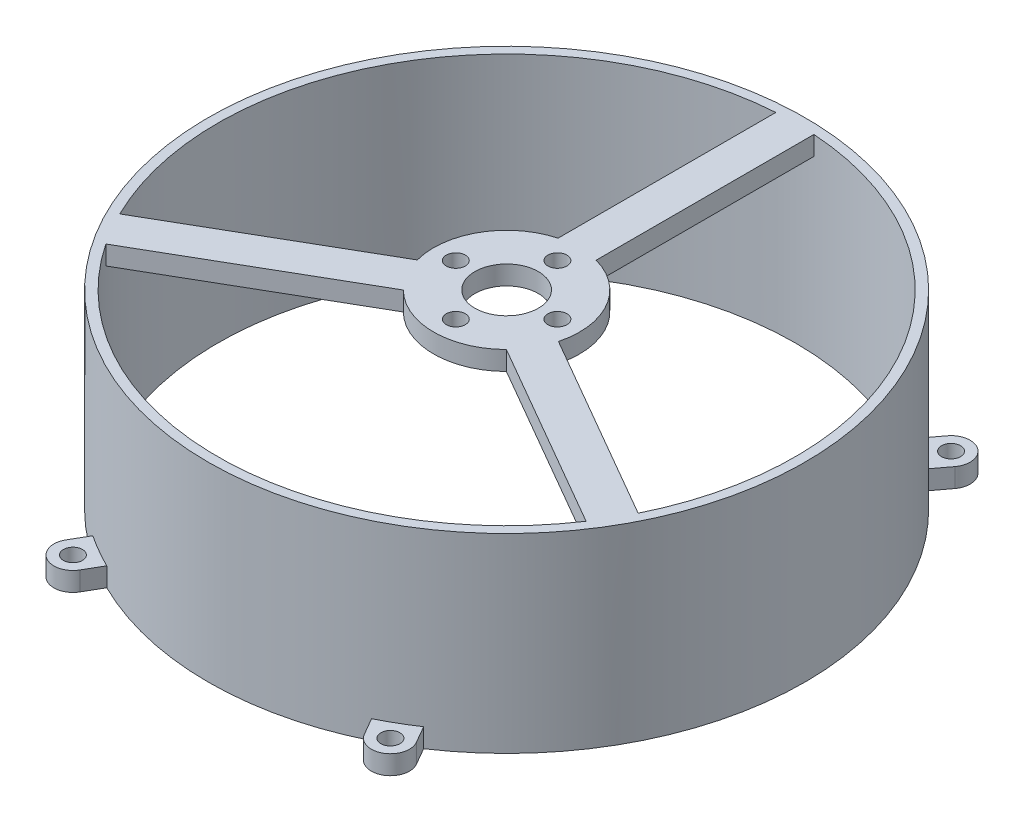
SolidWorks part; units mm, degrees
ref_plane "前视基准面" through (0, 0, 0) normal (0, 0, 1) x (1, 0, 0)
ref_plane "上视基准面" through (0, 0, 0) normal (0, 1, 0) x (1, 0, 0)
ref_plane "右视基准面" through (0, 0, 0) normal (1, 0, 0) x (0, 0, -1)
sketch "草图1" plane through (0, 0, 0) normal (0, 1, 0) x (1, 0, 0)
  circle A21 centre (0, 0) radius 45
  circle A22 centre (0, 0) radius 47
  dimension "D1" = 90
  dimension "D2" = 2
extrude "凸台-拉伸1" add sketch "草图1" along normal blind 30
sketch "草图2" plane through (0, 0, 0) normal (0, -1, 0) x (-1, 0, 0)
  line L0 (25, -43.3013) -> (22.5, -38.9711) construction
  line L1 (22.4019, -44.8013) -> (19.8519, -40.3844)
  line L2 (27.5981, -41.8013) -> (25.048, -37.3844)
  line L3 (0, 0) -> (0, -60.2542) construction
  line L4 (-25, -43.3013) -> (-22.5, -38.9711) construction
  line L5 (-27.5981, -41.8013) -> (-25.048, -37.3844)
  line L6 (-22.4019, -44.8013) -> (-19.8519, -40.3844)
  line L7 (30, 40) -> (27, 36) construction
  line L8 (32.4, 38.2) -> (29.3399, 34.1199)
  line L9 (27.6, 41.8) -> (24.5399, 37.7199)
  line L10 (-30, 40) -> (-27, 36) construction
  line L11 (-27.6, 41.8) -> (-24.5399, 37.7199)
  line L12 (-32.4, 38.2) -> (-29.3399, 34.1199)
  circle A0 centre (25, -43.3013) radius 1.5
  circle A1 centre (0, 0) radius 47 construction
  arc A2 (22.4019, -44.8013) -> (27.5981, -41.8013) centre (25, -43.3013) ccw
  arc A4 (19.8519, -40.3844) -> (25.048, -37.3844) centre (0, 0) ccw
  arc A5 (-22.4019, -44.8013) -> (-27.5981, -41.8013) centre (-25, -43.3013) cw
  circle A6 centre (-25, -43.3013) radius 1.5
  circle A7 centre (30, 40) radius 1.5
  arc A8 (32.4, 38.2) -> (27.6, 41.8) centre (30, 40) ccw
  arc A10 (29.3399, 34.1199) -> (24.5399, 37.7199) centre (0, 0) ccw
  arc A11 (-32.4, 38.2) -> (-27.6, 41.8) centre (-30, 40) cw
  circle A12 centre (-30, 40) radius 1.5
  arc A13 (-24.5399, 37.7199) -> (-29.3399, 34.1199) centre (0, 0) ccw
  arc A14 (-25.048, -37.3844) -> (-19.8519, -40.3844) centre (0, 0) ccw
  point P4 (12.5, -21.6506)
  point P21 (15, 20)
  dimension "D1" = 3
  dimension "D2" = 50
  dimension "D3" = 3
  dimension "D4" = 50
  dimension "D5" = 3
  dimension "D6" = 3
  dimension "D7" = 30
extrude "凸台-拉伸5" add sketch "草图2" against normal blind 3
sketch "草图3" plane through (0, 30, 0) normal (0, 1, 0) x (1, 0, 0)
  line L0 (-3, 44.8999) -> (-3, 11.1018)
  line L1 (0, 11.5) -> (0, 45) construction
  line L2 (3, 44.8999) -> (3, 11.1018)
  line L3 (40.3844, -19.8519) -> (11.1144, -2.9528)
  line L4 (37.3844, -25.048) -> (8.1144, -8.149)
  line L5 (-37.3844, -25.048) -> (-8.1144, -8.149)
  line L6 (-40.3844, -19.8519) -> (-11.1144, -2.9528)
  circle A0 centre (0, 0) radius 5
  circle A1 centre (8, 0) radius 1.5
  circle A3 centre (0, -8) radius 1.5
  circle A4 centre (-8, 0) radius 1.5
  circle A5 centre (0, 8) radius 1.5
  arc A6 (11.1144, -2.9528) -> (3, 11.1018) centre (0, 0) ccw
  circle A7 centre (0, 0) radius 45 construction
  arc A8 (3, 44.8999) -> (-3, 44.8999) centre (0, 0) ccw
  arc A9 (-8.1144, -8.149) -> (8.1144, -8.149) centre (0, 0) ccw
  arc A10 (-3, 11.1018) -> (-11.1144, -2.9528) centre (0, 0) ccw
  arc A11 (-40.3844, -19.8519) -> (-37.3844, -25.048) centre (0, 0) ccw
  arc A12 (37.3844, -25.048) -> (40.3844, -19.8519) centre (0, 0) ccw
  point P14 (0, 0)
  point P32 (0, 0)
  dimension "D1" = 10
  dimension "D2" = 3
  dimension "D3" = 8
  dimension "D4" = 23
  dimension "D5" = 3
extrude "凸台-拉伸6" add sketch "草图3" against normal blind 3
sketch "草图4" plane through (0, 0, 0) normal (0, -1, 0) x (1, 0, 0)
  line L0 (-37.3844, 25.048) -> (-37.8184, 25.2986)
  line L1 (-37.3844, 25.048) -> (-8.1144, 8.149) construction
  line L2 (-40.3844, 19.8519) -> (-40.8184, 20.1024)
  line L3 (-11.1144, 2.9528) -> (-40.3844, 19.8519) construction
  line L4 (37.3844, 25.048) -> (37.8184, 25.2986)
  line L5 (8.1144, 8.149) -> (37.3844, 25.048) construction
  line L6 (40.3844, 19.8519) -> (40.8184, 20.1024)
  line L8 (-3, -44.8999) -> (-3, -45.401)
  line L10 (3, -44.8999) -> (3, -45.401)
  arc A0 (-40.8184, 20.1024) -> (-3, -45.401) centre (0, 0) ccw
  circle A1 centre (0, 0) radius 45 construction
  arc A2 (-40.3844, 19.8519) -> (-3, -44.8999) centre (0, 0) ccw
  arc A3 (37.8184, 25.2986) -> (-37.8184, 25.2986) centre (0, 0) ccw
  arc A4 (37.3844, 25.048) -> (-37.3844, 25.048) centre (0, 0) ccw
  arc A5 (3, -45.401) -> (40.8184, 20.1024) centre (0, 0) ccw
  arc A6 (3, -44.8999) -> (40.3844, 19.8519) centre (0, 0) ccw
  dimension "D1" = 0.5
extrude "切除-拉伸1" cut sketch "草图4" against normal up to surface (30 mm away) up to face at (19.42, 30, -11.2121)
sketch "草图5" plane through (0, 27, 0) normal (0, -1, 0) x (-1, 0, 0)
  circle A0 centre (0, 0) radius 45.5
extrude "切除-拉伸2" cut sketch "草图5" along normal blind 44
